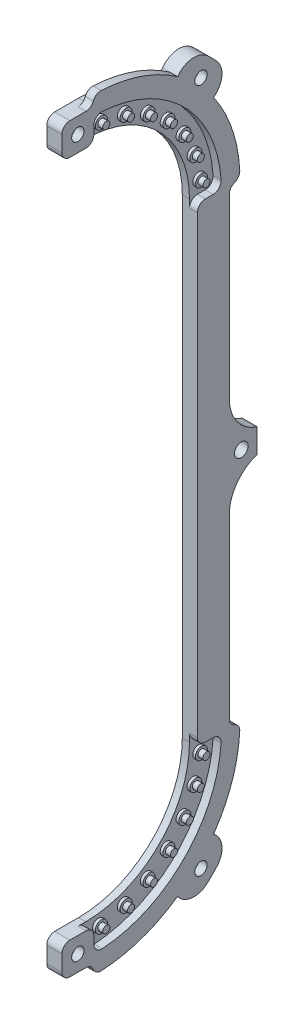
SolidWorks part; units mm, degrees
material "PVC 0.007 塑化"
ref_plane "前视基准面" through (0, 0, 0) normal (0, 0, 1) x (1, 0, 0)
ref_plane "上视基准面" through (0, 0, 0) normal (0, 1, 0) x (1, 0, 0)
ref_plane "右视基准面" through (0, 0, 0) normal (1, 0, 0) x (0, 0, -1)
sketch "草图1" plane through (0, 0, 0) normal (1, 0, 0) x (0, 0, -1)
  line L5 (0, 26) -> (0, 0) construction
  line L6 (0, 26) -> (-8, 26)
  line L11 (0, 26) -> (0, 34) construction
  line L12 (0, 34) -> (-8, 34)
  line L15 (-8, 26) -> (-8, 34)
  line L20 (0, 26) -> (-8, 34) construction
  line L21 (0, 34) -> (-8, 26) construction
  line L22 (26, 0) -> (34, 0) construction
  line L24 (26, -59.01) -> (34, -59.01) construction
  line L26 (26, 0) -> (34, -59.01) construction
  line L27 (26, -59.01) -> (34, 0) construction
  line L28 (0, 0) -> (26, 0) construction
  line L29 (0, 0) -> (18.3848, 18.3848) construction
  line L30 (18.3848, 18.3848) -> (24.0416, 24.0416) construction
  line L31 (0, 0) -> (19.5016, 27.8512) construction
  line L32 (0, 0) -> (27.8512, 19.5016) construction
  line L33 (24.0416, 24.0416) -> (29.6985, 29.6985) construction
  line L35 (19.5016, 27.8512) -> (24.0902, 34.4044)
  line L36 (27.8512, 19.5016) -> (34.4044, 24.0902)
  line L42 (26, 0) -> (26, -59.01)
  line L43 (34, 0) -> (34, -59.01)
  line L44 (26, -59.01) -> (34, -59.01)
  line L46 (26, -59.01) -> (34, -59.01) construction
  line L47 (26, -59.01) -> (26, -51.01) construction
  line L48 (26, -51.01) -> (34, -51.01) construction
  line L49 (34, -59.01) -> (34, -51.01) construction
  line L50 (26, -59.01) -> (34, -51.01) construction
  line L51 (26, -51.01) -> (34, -59.01) construction
  arc A6 (26, 0) -> (0, 26) centre (0, 0) ccw
  arc A7 (34, 0) -> (27.8512, 19.5016) centre (0, 0) ccw
  circle A9 centre (-4, 30) radius 1.65
  arc A10 (34.4044, 24.0902) -> (24.0902, 34.4044) centre (0, 0) ccw
  circle A11 centre (26.8701, 26.8701) radius 1.65
  arc A12 (19.5016, 27.8512) -> (0, 34) centre (0, 0) ccw
  arc A13 (19.5016, 27.8512) -> (24.0416, 24.0416) centre (0, 0) cw construction
  circle A92 centre (30, -55.01) radius 1.65
  point P8 (-4, 30)
  point P13 (30, -29.505)
  point P38 (30, -55.01)
  point P100 (0, 0)
  dimension "D1" = 52
  dimension "D2" = 68
  dimension "D5" = 59.01
  dimension "D3" = 3.3
  dimension "D6" = 3.3
  dimension "D7" = 84
  dimension "D10" = 3.3
  dimension "D4" = 8
  dimension "D8" = 10
  dimension "D9" = 10
  dimension "D13" = 8
extrude "凸台-拉伸1" add sketch "草图1" along normal blind 1.8
fillet "圆角1" radius 5 2 edges at (0.9, 24.0902, -34.4044) (0.9, 34.4044, -24.0902)
fillet "圆角2" radius 2 4 edges at (0.9, 19.5016, -27.8512) (0.9, 27.8512, -19.5016) (0.9, 26, 8) (0.9, 34, 8)
sketch "草图2" plane through (1.8, 0, 0) normal (1, 0, 0) x (0, 0, -1)
  line L0 (0, 26) -> (0, 32)
  line L1 (32, 0) -> (26, 0)
  line L2 (36.6606, 0) -> (34, 0)
  line L3 (0, 36.6606) -> (0, 34)
  line L8 (26, -59.01) -> (34, -59.01)
  line L9 (34, -59.01) -> (34, 0)
  line L10 (29.4439, 20.6169) -> (30.0306, 21.0277)
  line L11 (21.0277, 30.0306) -> (20.6169, 29.4439)
  line L12 (0, 34) -> (-6, 34)
  line L13 (-8, 32) -> (-8, 28)
  line L14 (-6, 26) -> (0, 26)
  line L15 (26, 0) -> (26, -59.01)
  line L16 (26, -59.01) -> (34, -59.01)
  line L17 (34, -59.01) -> (34, 0)
  line L18 (29.4439, 20.6169) -> (30.0306, 21.0277) construction
  line L19 (21.0277, 30.0306) -> (20.6169, 29.4439) construction
  line L20 (0, 34) -> (-6, 34)
  line L21 (-8, 32) -> (-8, 28)
  line L22 (-6, 26) -> (0, 26)
  line L23 (26, 0) -> (26, -59.01)
  arc A0 (0, 32) -> (32, 0) centre (0, 0) cw
  arc A1 (21.0277, 30.0306) -> (0, 36.6606) centre (0, 0) ccw
  arc A2 (30.0306, 21.0277) -> (36.6606, 0) centre (0, 0) cw
  circle A3 centre (-4, 30) radius 1.55
  circle A4 centre (26.8701, 26.8701) radius 1.55
  circle A5 centre (30, -55.01) radius 1.55
  arc A13 (34, 0) -> (28.8916, 17.9242) centre (0, 0) ccw
  arc A14 (29.4439, 20.6169) -> (28.8916, 17.9242) centre (30.5911, 18.9786) ccw
  arc A15 (30.0306, 21.0277) -> (30.8334, 28.5185) centre (27.1627, 25.1234) ccw
  arc A16 (30.8334, 28.5185) -> (28.5185, 30.8334) centre (0, 0) ccw
  arc A17 (28.5185, 30.8334) -> (21.0277, 30.0306) centre (25.1234, 27.1627) ccw
  arc A18 (17.9242, 28.8916) -> (20.6169, 29.4439) centre (18.9786, 30.5911) ccw
  arc A19 (17.9242, 28.8916) -> (0, 34) centre (0, 0) ccw
  arc A20 (-6, 34) -> (-8, 32) centre (-6, 32) ccw
  arc A21 (-8, 28) -> (-6, 26) centre (-6, 28) ccw
  arc A22 (26, 0) -> (0, 26) centre (0, 0) ccw
  arc A25 (34, 0) -> (28.8916, 17.9242) centre (0, 0) ccw construction
  arc A26 (29.4439, 20.6169) -> (28.8916, 17.9242) centre (30.5911, 18.9786) ccw construction
  arc A27 (30.0306, 21.0277) -> (30.8334, 28.5185) centre (27.1627, 25.1234) ccw
  arc A28 (30.8334, 28.5185) -> (28.5185, 30.8334) centre (0, 0) ccw
  arc A29 (28.5185, 30.8334) -> (21.0277, 30.0306) centre (25.1234, 27.1627) ccw
  arc A30 (17.9242, 28.8916) -> (20.6169, 29.4439) centre (18.9786, 30.5911) ccw construction
  arc A31 (17.9242, 28.8916) -> (0, 34) centre (0, 0) ccw construction
  arc A32 (-6, 34) -> (-8, 32) centre (-6, 32) ccw
  arc A33 (-8, 28) -> (-6, 26) centre (-6, 28) ccw
  arc A34 (26, 0) -> (0, 26) centre (0, 0) ccw construction
  dimension "D3" = 3.1
  dimension "D4" = 3.1
  dimension "D5" = 3.1
  dimension "D2" = 6
  dimension "D1" = 0
extrude "凸台-拉伸2" add sketch "草图2" along normal blind 2
fillet "圆角3" radius 2 6 edges at (2.8, 0, -26) (2.8, 0, -34) (2.8, 0, -32) (2.8, 26, 0) (2.8, 32, 0) (2.8, 34, 0)
fillet "圆角4" radius 2 2 edges at (2.8, 0, -36.6606) (2.8, 36.6606, 0)
sketch "草图3" plane through (1.8, 0, 0) normal (1, 0, 0) x (0, 0, -1)
  line L0 (0, 0) -> (22.6274, 22.6274) construction
  line L1 (18.3848, 18.3848) -> (21.9203, 21.9203) construction
  line L2 (0, 0) -> (20.1525, 20.1525) construction
  arc A0 (31.9288, 2.1333) -> (2.1333, 31.9288) centre (0, 0) ccw construction
  arc A1 (26, 0) -> (0, 26) centre (0, 0) ccw construction
  circle A2 centre (20.1525, 20.1525) radius 1.5
  circle A3 centre (24.1316, 15.1629) radius 1.5
  circle A4 centre (26.9007, 9.413) radius 1.5
  circle A5 centre (28.3208, 3.191) radius 1.5
  circle A27 centre (3.191, 28.3208) radius 1.5
  circle A28 centre (9.413, 26.9007) radius 1.5
  circle A29 centre (15.1629, 24.1316) radius 1.5
  circle A30 centre (26.9007, -9.413) radius 1.5 [skipped]
  circle A31 centre (24.1316, -15.1629) radius 1.5 [skipped]
  circle A32 centre (20.1525, -20.1525) radius 1.5 [skipped]
  circle A33 centre (15.1629, -24.1316) radius 1.5 [skipped]
  circle A34 centre (9.413, -26.9007) radius 1.5 [skipped]
  circle A35 centre (3.191, -28.3208) radius 1.5 [skipped]
  circle A36 centre (-3.191, -28.3208) radius 1.5 [skipped]
  circle A37 centre (-9.413, -26.9007) radius 1.5 [skipped]
  circle A38 centre (-15.1629, -24.1316) radius 1.5 [skipped]
  circle A39 centre (-20.1525, -20.1525) radius 1.5 [skipped]
  circle A40 centre (-24.1316, -15.1629) radius 1.5 [skipped]
  circle A41 centre (-26.9007, -9.413) radius 1.5 [skipped]
  circle A42 centre (28.3208, -3.191) radius 1.5 [skipped]
  circle A43 centre (-28.3208, -3.191) radius 1.5 [skipped]
  circle A44 centre (-28.3208, 3.191) radius 1.5 [skipped]
  circle A45 centre (-26.9007, 9.413) radius 1.5 [skipped]
  circle A46 centre (-24.1316, 15.1629) radius 1.5 [skipped]
  circle A47 centre (-20.1525, 20.1525) radius 1.5 [skipped]
  circle A48 centre (-3.191, 28.3208) radius 1.5 [skipped]
  circle A49 centre (-9.413, 26.9007) radius 1.5 [skipped]
  circle A50 centre (-15.1629, 24.1316) radius 1.5 [skipped]
  dimension "D2" = 3
  dimension "D1" = 5
  dimension "D3" = 28.5
  dimension "D4" = 28
extrude "凸台-拉伸3" add sketch "草图3" along normal blind 0.7
sketch "草图4" plane through (2.5, 0, 0) normal (1, 0, 0) x (0, 0, -1)
  circle A0 centre (3.191, 28.3208) radius 0.9
  circle A1 centre (9.413, 26.9007) radius 0.9
  circle A2 centre (15.1629, 24.1316) radius 0.9
  circle A3 centre (20.1525, 20.1525) radius 0.9
  circle A4 centre (24.1316, 15.1629) radius 0.9
  circle A5 centre (26.9007, 9.413) radius 0.9
  circle A6 centre (28.3208, 3.191) radius 0.9
  dimension "D1" = 1.8
  dimension "D2" = 1.8
  dimension "D3" = 1.8
  dimension "D4" = 1.8
  dimension "D5" = 1.8
  dimension "D6" = 1.8
  dimension "D7" = 1.8
extrude "凸台-拉伸4" add sketch "草图4" along normal blind 1.25
sketch "草图5" plane through (0, 0, 0) normal (-1, 0, 0) x (0, 0, 1)
  circle A0 centre (-30, -55.01) radius 1.65 construction
  circle A1 centre (-30, -55.01) radius 1.65
extrude "凸台-拉伸5" add sketch "草图5" along direction (-1, 0, 0) on the side against the normal up to surface (3.8 mm away)
ref_plane "基准面1" through (0, -8, 0) normal (0, 1, 0) x (1, 0, 0)
mirror "镜向2" about plane through (1.8, -59.01, 0) normal (0, 1, 0) of "凸台-拉伸4", "凸台-拉伸5", "凸台-拉伸3", "圆角3", "圆角4", "凸台-拉伸2", "圆角2", "圆角1", "凸台-拉伸1"
sketch "草图6" plane through (0, 0, 0) normal (-1, 0, 0) x (0, 0, 1)
  line L0 (-26, -59.01) -> (-34, -59.01) construction
  line L1 (-26, 0) -> (-26, -118.02) construction
  line L2 (-34, 0) -> (-34, -118.02) construction
  line L3 (-34, -53.4622) -> (-41, -56.01)
  line L4 (-41, -56.01) -> (-41, -62.01)
  line L5 (-34, -64.5578) -> (-41, -62.01)
  line L6 (-34, -53.4622) -> (-34, -64.5578)
  circle A0 centre (-37, -59.01) radius 1.7
  point P10 (-41, -59.01)
  dimension "D1" = 3.4
  dimension "D2" = 3
  dimension "D3" = 7
  dimension "D4" = 6
  dimension "D5" = 70
extrude "凸台-拉伸7" add sketch "草图6" against normal up to surface (3.8 mm away) up to face at (3.8, -59.01, -14.1925)
fillet "圆角5" radius 10 2 edges at (1.9, -64.5578, -34) (1.9, -53.4622, -34)
